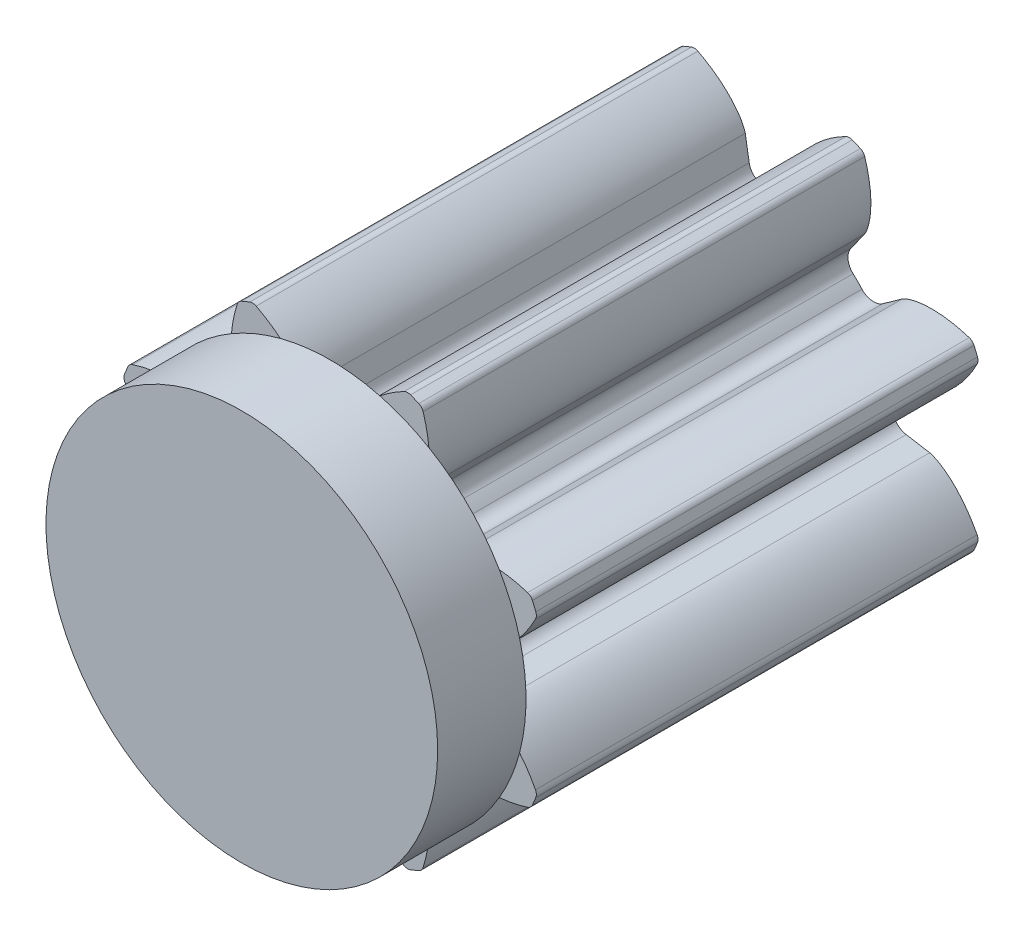
SolidWorks part; units mm, degrees
material "Alloy Steel"
ref_plane "Front" through (0, 0, 0) normal (0, 0, 1) x (1, 0, 0)
ref_plane "Top" through (0, 0, 0) normal (0, 1, 0) x (1, 0, 0)
ref_plane "Right" through (0, 0, 0) normal (1, 0, 0) x (0, 0, -1)
sketch "Sketch1" plane through (0, 0, 0) normal (0, 0, 1) x (1, 0, 0)
  circle A0 centre (0, 0) radius 6.35
extrude "Boss-Extrude1" add sketch "Sketch1" along normal blind 12.7
sketch "Sketch3" plane through (0, 0, 0) normal (0, 0, 1) x (1, 0, 0)
  line L0 (0, 0) -> (43.7181, 0) construction
  line L2 (0, 0) -> (-0.5784, 3.4443) construction
  line L3 (0, 0) -> (0.5784, 3.4443) construction
  line L4 (0.5784, 3.4443) -> (0.7625, 4.5405) construction
  line L5 (0, 0) -> (0, 61.276) construction
  line L6 (-0.5784, 3.4443) -> (-0.7625, 4.5405) construction
  circle A0 centre (0, 0) radius 6.35 construction
  circle A1 centre (0, 0) radius 5.08 construction
  circle A2 centre (0, 0) radius 4.604 construction
  arc A3 (0.5784, 3.4443) -> (-0.5784, 3.4443) centre (0, 0) ccw construction
  arc A5 (2.2164, 5.9506) -> (-2.2164, 5.9506) centre (0, 0) ccw
  spline S0 degree 4 poles (-0.7625, 4.5405) (-0.763, 4.5435) (-0.7648, 4.5519) (-0.7689, 4.5677) (-0.7767, 4.5932) (-0.7881, 4.6252) (-0.8045, 4.666) (-0.826, 4.7133) (-0.852, 4.7644) (-0.8825, 4.8189) (-0.9151, 4.8722) (-0.9496, 4.9244) (-0.9856, 4.9755) (-1.0311, 5.0363) (-1.0885, 5.1074) (-1.1594, 5.1881) (-1.2442, 5.2764) (-1.3353, 5.3629) (-1.4285, 5.4451) (-1.5269, 5.5244) (-1.6249, 5.5987) (-1.7306, 5.6719) (-1.8302, 5.7375) (-1.9458, 5.8065) (-2.0404, 5.8609) (-2.1692, 5.9277) (-2.2466, 5.9657) (-2.3384, 6.0084) (-2.3799, 6.0264) (-2.4054, 6.0376) knots 0 0 0 0 0 0.005377 0.015084 0.028532 0.04661 0.064855 0.092111 0.119476 0.146842 0.174209 0.201575 0.228941 0.256307 0.307035 0.361767 0.4165 0.471232 0.525964 0.580697 0.635429 0.690161 0.744894 0.799626 0.854358 0.909091 0.954545 1 1 1 1 1 construction
  spline S1 degree 4 poles (-0.7625, 4.5405) (-0.763, 4.5435) (-0.7648, 4.5519) (-0.7689, 4.5677) (-0.7767, 4.5932) (-0.7881, 4.6252) (-0.8045, 4.666) (-0.826, 4.7133) (-0.852, 4.7644) (-0.8825, 4.8189) (-0.9151, 4.8722) (-0.9496, 4.9244) (-0.9856, 4.9755) (-1.0311, 5.0363) (-1.0885, 5.1074) (-1.1594, 5.1881) (-1.2442, 5.2764) (-1.3353, 5.3629) (-1.4285, 5.4451) (-1.5269, 5.5244) (-1.6249, 5.5987) (-1.7306, 5.6719) (-1.8302, 5.7375) (-1.9458, 5.8065) (-2.0404, 5.8609) (-2.1413, 5.9133) (-2.1909, 5.9381) (-2.2164, 5.9506) knots 0 0 0 0 0 0.005377 0.015084 0.028532 0.04661 0.064855 0.092111 0.119476 0.146842 0.174209 0.201575 0.228941 0.256307 0.307035 0.361767 0.4165 0.471232 0.525964 0.580697 0.635429 0.690161 0.744894 0.799626 0.854358 0.909091 0.909091 0.909091 0.909091 0.909091
  spline S2 degree 4 poles (0.7625, 4.5405) (0.763, 4.5435) (0.7648, 4.5519) (0.7689, 4.5677) (0.7767, 4.5932) (0.7881, 4.6252) (0.8045, 4.666) (0.826, 4.7133) (0.852, 4.7644) (0.8825, 4.8189) (0.9151, 4.8722) (0.9496, 4.9244) (0.9856, 4.9755) (1.0311, 5.0363) (1.0885, 5.1074) (1.1594, 5.1881) (1.2442, 5.2764) (1.3353, 5.3629) (1.4285, 5.4451) (1.5269, 5.5244) (1.6249, 5.5987) (1.7306, 5.6719) (1.8302, 5.7375) (1.9458, 5.8065) (2.0404, 5.8609) (2.1692, 5.9277) (2.2466, 5.9657) (2.3384, 6.0084) (2.3799, 6.0264) (2.4054, 6.0376) knots 0 0 0 0 0 0.005377 0.015084 0.028532 0.04661 0.064855 0.092111 0.119476 0.146842 0.174209 0.201575 0.228941 0.256307 0.307035 0.361767 0.4165 0.471232 0.525964 0.580697 0.635429 0.690161 0.744894 0.799626 0.854358 0.909091 0.954545 1 1 1 1 1 construction
  spline S3 degree 4 poles (0.7625, 4.5405) (0.763, 4.5435) (0.7648, 4.5519) (0.7689, 4.5677) (0.7767, 4.5932) (0.7881, 4.6252) (0.8045, 4.666) (0.826, 4.7133) (0.852, 4.7644) (0.8825, 4.8189) (0.9151, 4.8722) (0.9496, 4.9244) (0.9856, 4.9755) (1.0311, 5.0363) (1.0885, 5.1074) (1.1594, 5.1881) (1.2442, 5.2764) (1.3353, 5.3629) (1.4285, 5.4451) (1.5269, 5.5244) (1.6249, 5.5987) (1.7306, 5.6719) (1.8302, 5.7375) (1.9458, 5.8065) (2.0404, 5.8609) (2.1413, 5.9133) (2.1909, 5.9381) (2.2164, 5.9506) knots 0 0 0 0 0 0.005377 0.015084 0.028532 0.04661 0.064855 0.092111 0.119476 0.146842 0.174209 0.201575 0.228941 0.256307 0.307035 0.361767 0.4165 0.471232 0.525964 0.580697 0.635429 0.690161 0.744894 0.799626 0.854358 0.909091 0.909091 0.909091 0.909091 0.909091
  point P0 (0, 3.4925)
sketch "DCLTBC" plane through (0, 0, 0) normal (0, 0, 1) x (1, 0, 0)
  line L0 (0, 0) -> (41.04, 0) construction
  line L1 (-0.5784, 3.4443) -> (-0.7625, 4.5405) construction
  line L2 (0.5784, 3.4443) -> (0.7625, 4.5405) construction
  line L3 (-0.5784, 3.4443) -> (-0.7625, 4.5405)
  line L4 (0.5784, 3.4443) -> (0.7625, 4.5405)
  line L5 (0, 0) -> (0, 104.9356) construction
  circle A0 centre (0, 0) radius 6.35
  circle A1 centre (0, 0) radius 5.08 construction
  circle A2 centre (0, 0) radius 4.604 construction
  arc A3 (0.5784, 3.4443) -> (-0.5784, 3.4443) centre (0, 0) ccw construction
  arc A4 (0.5784, 3.4443) -> (-0.5784, 3.4443) centre (0, 0) ccw
  spline S0 degree 4 poles (-985.3765, -170.0538) (-13.2322, 1.3996) (-0.8474, 3.8586) (-0.6755, 4.2604) (-0.7767, 4.5932) (-0.7881, 4.6252) (-0.8045, 4.666) (-0.826, 4.7133) (-0.852, 4.7644) (-0.8825, 4.8189) (-0.9151, 4.8722) (-0.9496, 4.9244) (-0.9856, 4.9755) (-1.0311, 5.0363) (-1.0885, 5.1074) (-1.1594, 5.1881) (-1.2442, 5.2764) (-1.3353, 5.3629) (-1.4285, 5.4451) (-1.5269, 5.5244) (-1.6249, 5.5987) (-1.7306, 5.6719) (-1.8302, 5.7375) (-1.9458, 5.8065) (-2.4469, 6.0948) (-4.2835, 6.892) (20.1681, -5.2427) (-900.8438, 444.5764) knots -0.5622 -0.5622 -0.5622 -0.5622 -0.5622 0.005377 0.015084 0.028532 0.04661 0.064855 0.092111 0.119476 0.146842 0.174209 0.201575 0.228941 0.256307 0.307035 0.361767 0.4165 0.471232 0.525964 0.580697 0.635429 0.690161 0.744894 0.799626 0.854358 1.850205 1.850205 1.850205 1.850205 1.850205 only from (-0.7625, 4.5405) to (-2.2164, 5.9506) construction
  spline S1 degree 4 poles (985.3765, -170.0538) (13.2322, 1.3996) (0.8474, 3.8586) (0.6755, 4.2604) (0.7767, 4.5932) (0.7881, 4.6252) (0.8045, 4.666) (0.826, 4.7133) (0.852, 4.7644) (0.8825, 4.8189) (0.9151, 4.8722) (0.9496, 4.9244) (0.9856, 4.9755) (1.0311, 5.0363) (1.0885, 5.1074) (1.1594, 5.1881) (1.2442, 5.2764) (1.3353, 5.3629) (1.4285, 5.4451) (1.5269, 5.5244) (1.6249, 5.5987) (1.7306, 5.6719) (1.8302, 5.7375) (1.9458, 5.8065) (2.4469, 6.0948) (4.2835, 6.892) (-20.1681, -5.2427) (900.8438, 444.5764) knots -0.5622 -0.5622 -0.5622 -0.5622 -0.5622 0.005377 0.015084 0.028532 0.04661 0.064855 0.092111 0.119476 0.146842 0.174209 0.201575 0.228941 0.256307 0.307035 0.361767 0.4165 0.471232 0.525964 0.580697 0.635429 0.690161 0.744894 0.799626 0.854358 1.850205 1.850205 1.850205 1.850205 1.850205 only from (0.7625, 4.5405) to (2.2164, 5.9506) construction
  spline S2 degree 4 poles (-0.7625, 4.5405) (-0.763, 4.5435) (-0.7648, 4.5519) (-0.7689, 4.5677) (-0.7767, 4.5932) (-0.7881, 4.6252) (-0.8045, 4.666) (-0.826, 4.7133) (-0.852, 4.7644) (-0.8825, 4.8189) (-0.9151, 4.8722) (-0.9496, 4.9244) (-0.9856, 4.9755) (-1.0311, 5.0363) (-1.0885, 5.1074) (-1.1594, 5.1881) (-1.2442, 5.2764) (-1.3353, 5.3629) (-1.4285, 5.4451) (-1.5269, 5.5244) (-1.6249, 5.5987) (-1.7306, 5.6719) (-1.8302, 5.7375) (-1.9458, 5.8065) (-2.0404, 5.8609) (-2.1413, 5.9133) (-2.1909, 5.9381) (-2.2164, 5.9506) knots 0 0 0 0 0 0.005377 0.015084 0.028532 0.04661 0.064855 0.092111 0.119476 0.146842 0.174209 0.201575 0.228941 0.256307 0.307035 0.361767 0.4165 0.471232 0.525964 0.580697 0.635429 0.690161 0.744894 0.799626 0.854358 0.909091 0.909091 0.909091 0.909091 0.909091
  spline S3 degree 4 poles (0.7625, 4.5405) (0.763, 4.5435) (0.7648, 4.5519) (0.7689, 4.5677) (0.7767, 4.5932) (0.7881, 4.6252) (0.8045, 4.666) (0.826, 4.7133) (0.852, 4.7644) (0.8825, 4.8189) (0.9151, 4.8722) (0.9496, 4.9244) (0.9856, 4.9755) (1.0311, 5.0363) (1.0885, 5.1074) (1.1594, 5.1881) (1.2442, 5.2764) (1.3353, 5.3629) (1.4285, 5.4451) (1.5269, 5.5244) (1.6249, 5.5987) (1.7306, 5.6719) (1.8302, 5.7375) (1.9458, 5.8065) (2.0404, 5.8609) (2.1413, 5.9133) (2.1909, 5.9381) (2.2164, 5.9506) knots 0 0 0 0 0 0.005377 0.015084 0.028532 0.04661 0.064855 0.092111 0.119476 0.146842 0.174209 0.201575 0.228941 0.256307 0.307035 0.361767 0.4165 0.471232 0.525964 0.580697 0.635429 0.690161 0.744894 0.799626 0.854358 0.909091 0.909091 0.909091 0.909091 0.909091
extrude "Cut-Extrude-DCLTBC" cut sketch "DCLTBC" along normal through all
fillet "Fillet-Tip-DCLTBC" radius 0.2258 2 edges at (2.2164, 5.9506, 6.35) (-2.2164, 5.9506, 6.35)
fillet "Fillet-Root-DCLTBC" radius 0.4517 2 edges at (-0.5784, 3.4443, 6.35) (0.5784, 3.4443, 6.35)
pattern_circular "CirPattern-DCLTBC" count 8 over 360 about axis through (0, 0, 12.7) along (0, 0, 1) of "Cut-Extrude-DCLTBC", "Fillet-Tip-DCLTBC", "Fillet-Root-DCLTBC"
sketch "DCGTBC" [suppressed] plane through (0, 0, 0) normal (0, 0, 1) x (1, 0, 0)
  line L0 (0, 0) -> (41.04, 0) construction
  line L1 (-48.5645, 4.2488) -> (0, 0) construction
  line L2 (0, 0) -> (48.5645, 4.2488) construction
  line L3 (0, 0) -> (-16.5124, 0)
  line L5 (0, 0) -> (0, 104.9356) construction
  circle A0 centre (0, 0) radius 51
  circle A1 centre (0, 0) radius 50 construction
  circle A2 centre (0, 0) radius 45.3154 construction
  arc A3 (-0.6955, 48.745) -> (0.6955, 48.745) centre (0, 0) ccw construction
  arc A11 (48.5645, 4.2488) -> (-48.5645, 4.2488) centre (0, 0) ccw
  spline S4 degree 4 poles (999.295, 35.0053) (13.8403, 43.0294) (-0.3845, 43.6678) (-0.691, 44.5628) (-0.6404, 45.4695) (-0.6324, 45.568) (-0.6192, 45.6953) (-0.6, 45.8451) (-0.575, 46.0098) (-0.5436, 46.1888) (-0.5087, 46.3672) (-0.4704, 46.545) (-0.4291, 46.7221) (-0.3755, 46.9363) (-0.3062, 47.1929) (-0.2177, 47.4924) (-0.1086, 47.8314) (0.0119, 48.1762) (0.1381, 48.5148) (0.2744, 48.8561) (0.4125, 49.1858) (0.565, 49.5274) (0.7103, 49.8422) (0.8831, 50.1938) (1.4894, 51.401) (3.4482, 54.802) (-14.0283, 22.6362) (482.937, 927.3456) knots -0.499953 -0.499953 -0.499953 -0.499953 -0.499953 0.005377 0.015084 0.028532 0.04661 0.064855 0.092111 0.119476 0.146842 0.174209 0.201575 0.228941 0.256307 0.307035 0.361767 0.4165 0.471232 0.525964 0.580697 0.635429 0.690161 0.744894 0.799626 0.854358 1.622574 1.622574 1.622574 1.622574 1.622574 only from (-0.6465, 45.3108) to (1.2974, 50.9835) construction
  spline S5 degree 4 poles (-999.295, 35.0053) (-13.8403, 43.0294) (0.3845, 43.6678) (0.691, 44.5628) (0.6404, 45.4695) (0.6324, 45.568) (0.6192, 45.6953) (0.6, 45.8451) (0.575, 46.0098) (0.5436, 46.1888) (0.5087, 46.3672) (0.4704, 46.545) (0.4291, 46.7221) (0.3755, 46.9363) (0.3062, 47.1929) (0.2177, 47.4924) (0.1086, 47.8314) (-0.0119, 48.1762) (-0.1381, 48.5148) (-0.2744, 48.8561) (-0.4125, 49.1858) (-0.565, 49.5274) (-0.7103, 49.8422) (-0.8831, 50.1938) (-1.4894, 51.401) (-3.4482, 54.802) (14.0283, 22.6362) (-482.937, 927.3456) knots -0.499953 -0.499953 -0.499953 -0.499953 -0.499953 0.005377 0.015084 0.028532 0.04661 0.064855 0.092111 0.119476 0.146842 0.174209 0.201575 0.228941 0.256307 0.307035 0.361767 0.4165 0.471232 0.525964 0.580697 0.635429 0.690161 0.744894 0.799626 0.854358 1.622574 1.622574 1.622574 1.622574 1.622574 only from (0.6465, 45.3108) to (-1.2974, 50.9835) construction
  spline S6 degree 4 poles (-0.6465, 45.3108) (-0.6465, 45.3197) (-0.6463, 45.3448) (-0.6447, 45.3921) (-0.6404, 45.4695) (-0.6324, 45.568) (-0.6192, 45.6953) (-0.6, 45.8451) (-0.575, 46.0098) (-0.5436, 46.1888) (-0.5087, 46.3672) (-0.4704, 46.545) (-0.4291, 46.7221) (-0.3755, 46.9363) (-0.3062, 47.1929) (-0.2177, 47.4924) (-0.1086, 47.8314) (0.0119, 48.1762) (0.1381, 48.5148) (0.2744, 48.8561) (0.4125, 49.1858) (0.565, 49.5274) (0.7103, 49.8422) (0.8831, 50.1938) (1.0255, 50.4773) (1.1808, 50.7691) (1.2577, 50.911) (1.2974, 50.9835) knots 0 0 0 0 0 0.005377 0.015084 0.028532 0.04661 0.064855 0.092111 0.119476 0.146842 0.174209 0.201575 0.228941 0.256307 0.307035 0.361767 0.4165 0.471232 0.525964 0.580697 0.635429 0.690161 0.744894 0.799626 0.854358 0.909091 0.909091 0.909091 0.909091 0.909091
  spline S7 degree 4 poles (0.6465, 45.3108) (0.6465, 45.3197) (0.6463, 45.3448) (0.6447, 45.3921) (0.6404, 45.4695) (0.6324, 45.568) (0.6192, 45.6953) (0.6, 45.8451) (0.575, 46.0098) (0.5436, 46.1888) (0.5087, 46.3672) (0.4704, 46.545) (0.4291, 46.7221) (0.3755, 46.9363) (0.3062, 47.1929) (0.2177, 47.4924) (0.1086, 47.8314) (-0.0119, 48.1762) (-0.1381, 48.5148) (-0.2744, 48.8561) (-0.4125, 49.1858) (-0.565, 49.5274) (-0.7103, 49.8422) (-0.8831, 50.1938) (-1.0255, 50.4773) (-1.1808, 50.7691) (-1.2577, 50.911) (-1.2974, 50.9835) knots 0 0 0 0 0 0.005377 0.015084 0.028532 0.04661 0.064855 0.092111 0.119476 0.146842 0.174209 0.201575 0.228941 0.256307 0.307035 0.361767 0.4165 0.471232 0.525964 0.580697 0.635429 0.690161 0.744894 0.799626 0.854358 0.909091 0.909091 0.909091 0.909091 0.909091
  dimension "D1" = 5
  dimension "D2" = 5
extrude "Cut-Extrude-DCGTBC" [suppressed] cut sketch "DCGTBC" along normal through all
fillet "Fillet-Tip-DCGTBC" [suppressed] radius 0.2258
pattern_circular "CirPattern-DCGTBC" [suppressed] count 8 over 360
sketch "Sketch4" plane through (0, 0, 12.7) normal (0, 0, 1) x (1, 0, 0)
  circle A0 centre (0, 0) radius 5.6319
extrude "Boss-Extrude2" add sketch "Sketch4" along normal blind 2.54
equation "\"DiametralPitch\" = 20'Diametral Pitch"
equation "\"NumTeeth\"= 8'Number of Teeth"
equation "\"PressureAngle\" = 25deg'Pressure Angle"
equation "\"Addendum\"= 1 / \"DiametralPitch\"'Addendum"
equation "\"Dedendum\"= 1.25 / \"DiametralPitch\"'Dedendum"
equation "\"WorkingDepth\"= 2 / \"DiametralPitch\"'Working Depth - here for REF (Not used in building model)"
equation "\"WholeDepth\"= 2.25 / \"DiametralPitch\"'Whole Depth - here for REF (Not used in building model)"
equation "\"Clearance\"= .25 / \"DiametralPitch\"'Clearance"
equation "\"CircularPitch\"= pi / \"DiametralPitch\"'Circular Pitch - here for REF (Not used in building model)"
equation "\"PitchCircle\"= \"NumTeeth\" / \"DiametralPitch\"'Pitch Circle - or - Pitch Diameter"
equation "\"OutsideDiameter\"= ( \"NumTeeth\" + 2 ) / \"DiametralPitch\"'Outside Diameter"
equation "\"Fillet_Root\"= \"Clearance\" * cos ( \"PressureAngle\" ) * tan ( ( 90 + \"PressureAngle\" ) / 2 ) 'Fillet Root"
equation "\"AddendumCircle\"= \"PitchCircle\" + ( 2 * \"Addendum\" )'Addendum Circle - or - Addendum Diameter"
equation "\"DedendumCircle\"= \"PitchCircle\" - ( 2 * \"Dedendum\" )'Dedendum Circle - or - Dedendum Diameter"
equation "\"BaseCircle\"= \"PitchCircle\" * cos ( \"PressureAngle\" )'Base Circle - Base Diameter"
equation "\"PitchAngle\"= 360deg / \"NumTeeth\"'Pitch Angle"
equation "\"Alpha\"= sqr ( \"PitchCircle\" ^ 2 - \"BaseCircle\" ^ 2 ) / \"BaseCircle\" * 180 / PI - \"PressureAngle\"'Alpha - Used for Calculating Beta"
equation "\"Beta\"= ( \"PitchAngle\" / 4 - ( \"Alpha\" - 90 ) )'Beta - Used in definition of the parameters for the parametric equation driven curve"
equation "\"Gamma\"= ( \"PitchAngle\" / 4 - ( \"Alpha\" + 90 ) )'Gamma - Used in definition of the parameters for the parametric equation driven curve"
equation "\"Phi\"= sqr ( ( \"AddendumCircle\" / 2 ) ^ 2 - ( \"BaseCircle\" / 2 ) ^ 2 ) / ( \"BaseCircle\" / 2 )'Phi - Used in definition of the parameters for the parametric equation driven curve"
equation "\"DCGTBC\"= iif ( \"DedendumCircle\" > \"BaseCircle\" , \"unsuppressed\" , \"suppressed\" )'if Dedendum Circle IS GREATER THAN BaseCircle THEN UnsuppressORSuppress FEATURE"
equation "\"DCLTBC\"= iif ( \"DedendumCircle\" - .002 > \"BaseCircle\" , \"suppressed\" , \"unsuppressed\" )'if Dedendum Circle - .002 IS GREATER THAN BaseCircle THEN SuppressORUnsuppress FEATURE"
equation "\"Cut-Extrude-DCGTBC\"= iif ( \"DedendumCircle\" > \"BaseCircle\" , \"unsuppressed\" , \"suppressed\" )'if Dedendum Circle IS GREATER THAN BaseCircle THEN UnsuppressORSuppress FEATURE"
equation "\"Cut-Extrude-DCLTBC\"= iif ( \"DedendumCircle\" - .002 > \"BaseCircle\" , \"suppressed\" , \"unsuppressed\" )'if Dedendum Circle - .002 IS GREATER THAN BaseCircle THEN SuppressORUnsuppress FEATURE"
equation "\"CirPattern-DCGTBC\"= iif ( \"DedendumCircle\" > \"BaseCircle\" , \"unsuppressed\" , \"suppressed\" )'if Dedendum Circle IS GREATER THAN BaseCircle THEN UnsuppressORSuppress FEATURE"
equation "\"CirPattern-DCLTBC\"= iif ( \"DedendumCircle\" - .002 > \"BaseCircle\" , \"suppressed\" , \"unsuppressed\" )'if Dedendum Circle - .002 IS GREATER THAN BaseCircle THEN SuppressORUnsuppress FEATURE"
equation "\"Fillet-Tip-DCGTBC\"= iif ( \"DedendumCircle\" > \"BaseCircle\" , \"unsuppressed\" , \"suppressed\" )'if Dedendum Circle IS GREATER THAN BaseCircle THEN UnsuppressORSuppress FEATURE"
equation "\"Fillet-Tip-DCLTBC\"= iif ( \"DedendumCircle\" - .002 > \"BaseCircle\" , \"suppressed\" , \"unsuppressed\" )'if Dedendum Circle - .002 IS GREATER THAN BaseCircle THEN SuppressORUnsuppress FEATURE"
equation "\"Fillet-Root-DCLTBC\"= iif ( \"DedendumCircle\" - .002 > \"BaseCircle\" , \"suppressed\" , \"unsuppressed\" )'if Dedendum Circle - .002 IS GREATER THAN BaseCircle THEN SuppressORUnsuppress FEATURE"
equation "\"D1@CirPattern-DCGTBC\"= \"NumTeeth\"'Number of Teeth"
equation "\"D1@CirPattern-DCLTBC\"= \"NumTeeth\"'Number of Teeth"
equation "\"D1@Fillet-Tip-DCGTBC\"= \"Fillet_Root\" / 2 'Tip Rad For Large No of Teeth"
equation "\"D1@Fillet-Tip-DCLTBC\"=\"Fillet_Root\" / 2'Tip Rad For Small No of Teeth"
equation "\"D1@Fillet-Root-DCLTBC\"= \"Fillet_Root\"'Fillet Root"
